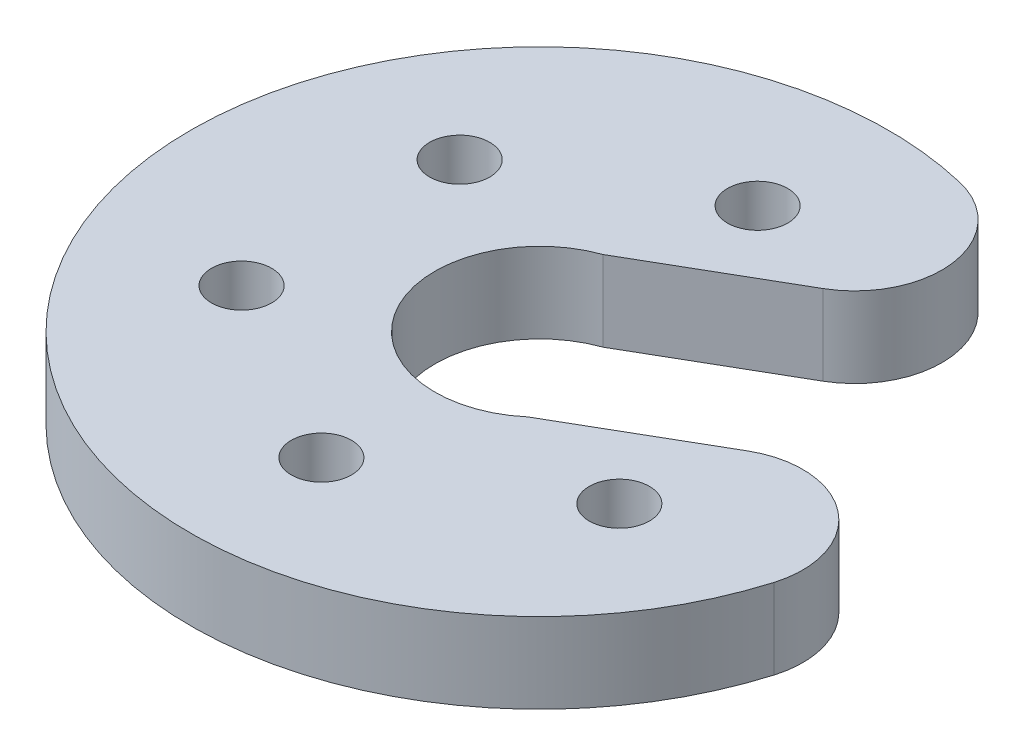
SolidWorks part; units mm, degrees
ref_plane "Front Plane" through (0, 0, 0) normal (0, 0, 1) x (1, 0, 0)
ref_plane "Top Plane" through (0, 0, 0) normal (0, 1, 0) x (1, 0, 0)
ref_plane "Right Plane" through (0, 0, 0) normal (1, 0, 0) x (0, 0, -1)
sketch "Sketch1" plane through (0, 0, 0) normal (0, 1, 0) x (1, 0, 0)
  circle A0 centre (0, 0) radius 20
  circle A1 centre (0, 0) radius 6
  circle A2 centre (0, 12.5) radius 1.725
  circle A3 centre (0, 0) radius 12.5 construction
  circle A4 centre (10.8253, 6.25) radius 1.725
  circle A5 centre (10.8253, -6.25) radius 1.725
  circle A6 centre (0, -12.5) radius 1.725
  circle A7 centre (-10.8253, -6.25) radius 1.725
  circle A8 centre (-10.8253, 6.25) radius 1.725
  point P19 (0, 0)
  dimension "D1" = 12
  dimension "D2" = 40
  dimension "D3" = 3.45
  dimension "D4" = 25
  dimension "D5" = 6
extrude "Boss-Extrude1" add sketch "Sketch1" along normal blind 4.6
sketch "Sketch2" plane through (0, 4.6, 0) normal (0, 1, 0) x (1, 0, 0)
  line L0 (0, 0) -> (10.8253, 6.25) construction
  line L1 (-2.0053, 5.655) -> (13.5997, 14.6645)
  line L2 (3.8947, -4.5641) -> (19.4997, 4.4454)
  arc A0 (3.8947, -4.5641) -> (-2.0053, 5.655) centre (0, 0) ccw
  circle A1 centre (0, 0) radius 6 construction
  circle A4 centre (10.8253, 6.25) radius 1.725 construction
  circle A5 centre (0, 0) radius 20 construction
  dimension "D1" = 11.8
  dimension "D2" = 5.9
extrude "Cut-Extrude1" cut sketch "Sketch2" against normal through all and the other way through all
fillet "Fillet2" radius 5 2 edges at (19.4997, 2.3, -4.4454) (13.5997, 2.3, -14.6645)
